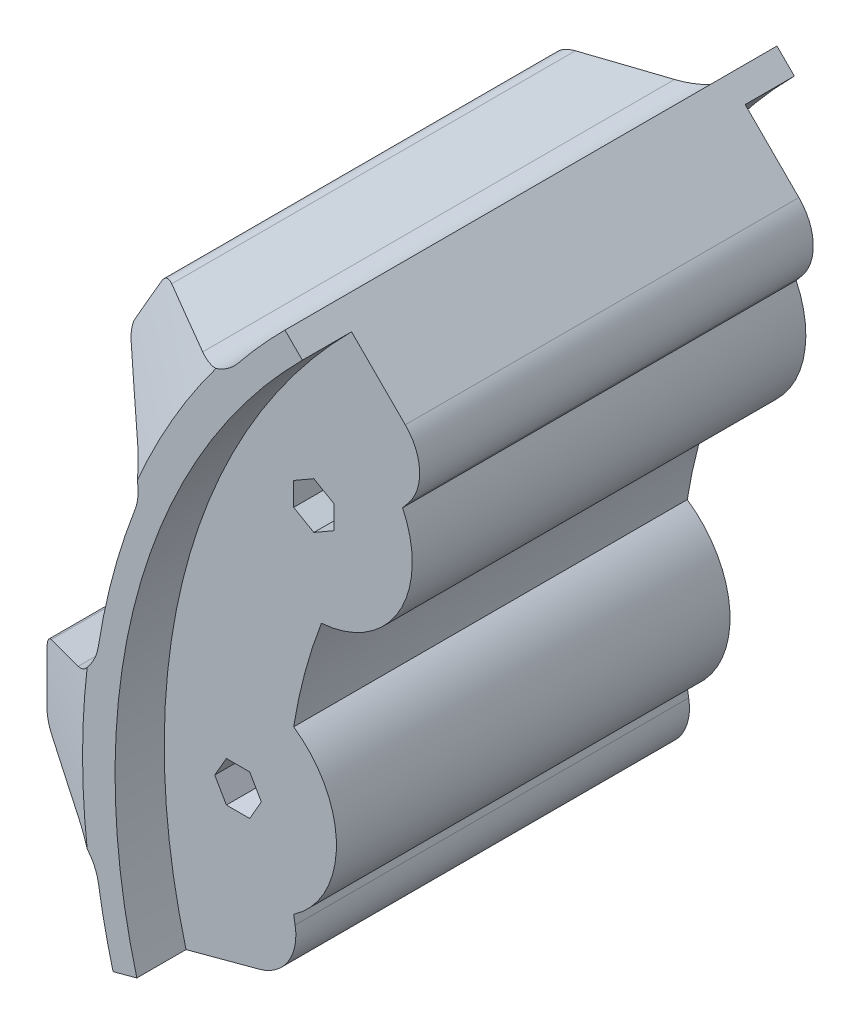
SolidWorks part; units mm, degrees
ref_plane "前视基准面" through (0, 0, 0) normal (0, 0, 1) x (1, 0, 0)
ref_plane "上视基准面" through (0, 0, 0) normal (0, 1, 0) x (1, 0, 0)
ref_plane "右视基准面" through (0, 0, 0) normal (1, 0, 0) x (0, 0, -1)
other "Configuration Table"
sketch "草图1" plane through (0, 0, 0) normal (0, 0, 1) x (1, 0, 0)
  circle A0 centre (0, 0) radius 115 construction
  circle A1 centre (0, 0) radius 105
  circle A2 centre (0, 0) radius 130
  dimension "D1" = 230
  dimension "D2" = 210
  dimension "D3" = 260
extrude "凸台-拉伸1" add sketch "草图1" along normal blind 80
sketch "草图2" plane through (0, 0, 80) normal (0, 0, 1) x (1, 0, 0)
  line L0 (62.2343, 99.5929) -> (59.8671, 103.6929)
  line L1 (4.1, 117.3671) -> (0, 119.7343)
  line L2 (0, 119.7343) -> (-4.1, 117.3671)
  line L3 (-4.1, 117.3671) -> (-4.1, 112.6329)
  line L4 (-4.1, 112.6329) -> (0, 110.2657)
  line L5 (0, 110.2657) -> (4.1, 112.6329)
  line L6 (4.1, 112.6329) -> (4.1, 117.3671)
  line L7 (59.8671, 95.4929) -> (62.2343, 99.5929)
  line L8 (55.1329, 95.4929) -> (59.8671, 95.4929)
  line L9 (52.7657, 99.5929) -> (55.1329, 95.4929)
  line L10 (55.1329, 103.6929) -> (52.7657, 99.5929)
  line L11 (59.8671, 103.6929) -> (55.1329, 103.6929)
  line L12 (103.6929, 55.1329) -> (103.6929, 59.8671)
  line L13 (99.5929, 52.7657) -> (103.6929, 55.1329)
  line L14 (95.4929, 55.1329) -> (99.5929, 52.7657)
  line L15 (95.4929, 59.8671) -> (95.4929, 55.1329)
  line L16 (99.5929, 62.2343) -> (95.4929, 59.8671)
  line L17 (103.6929, 59.8671) -> (99.5929, 62.2343)
  line L18 (117.3671, -4.1) -> (119.7343, 0)
  line L19 (112.6329, -4.1) -> (117.3671, -4.1)
  line L20 (110.2657, 0) -> (112.6329, -4.1)
  line L21 (112.6329, 4.1) -> (110.2657, 0)
  line L22 (117.3671, 4.1) -> (112.6329, 4.1)
  line L23 (119.7343, 0) -> (117.3671, 4.1)
  line L24 (99.5929, -62.2343) -> (103.6929, -59.8671)
  line L25 (95.4929, -59.8671) -> (99.5929, -62.2343)
  line L26 (95.4929, -55.1329) -> (95.4929, -59.8671)
  line L27 (99.5929, -52.7657) -> (95.4929, -55.1329)
  line L28 (103.6929, -55.1329) -> (99.5929, -52.7657)
  line L29 (103.6929, -59.8671) -> (103.6929, -55.1329)
  line L30 (55.1329, -103.6929) -> (59.8671, -103.6929)
  line L31 (52.7657, -99.5929) -> (55.1329, -103.6929)
  line L32 (55.1329, -95.4929) -> (52.7657, -99.5929)
  line L33 (59.8671, -95.4929) -> (55.1329, -95.4929)
  line L34 (62.2343, -99.5929) -> (59.8671, -95.4929)
  line L35 (59.8671, -103.6929) -> (62.2343, -99.5929)
  line L36 (-4.1, -117.3671) -> (0, -119.7343)
  line L37 (-4.1, -112.6329) -> (-4.1, -117.3671)
  line L38 (0, -110.2657) -> (-4.1, -112.6329)
  line L39 (4.1, -112.6329) -> (0, -110.2657)
  line L40 (4.1, -117.3671) -> (4.1, -112.6329)
  line L41 (0, -119.7343) -> (4.1, -117.3671)
  line L42 (-62.2343, -99.5929) -> (-59.8671, -103.6929)
  line L43 (-59.8671, -95.4929) -> (-62.2343, -99.5929)
  line L44 (-55.1329, -95.4929) -> (-59.8671, -95.4929)
  line L45 (-52.7657, -99.5929) -> (-55.1329, -95.4929)
  line L46 (-55.1329, -103.6929) -> (-52.7657, -99.5929)
  line L47 (-59.8671, -103.6929) -> (-55.1329, -103.6929)
  line L48 (-103.6929, -55.1329) -> (-103.6929, -59.8671)
  line L49 (-99.5929, -52.7657) -> (-103.6929, -55.1329)
  line L50 (-95.4929, -55.1329) -> (-99.5929, -52.7657)
  line L51 (-95.4929, -59.8671) -> (-95.4929, -55.1329)
  line L52 (-99.5929, -62.2343) -> (-95.4929, -59.8671)
  line L53 (-103.6929, -59.8671) -> (-99.5929, -62.2343)
  line L54 (-117.3671, 4.1) -> (-119.7343, 0)
  line L55 (-112.6329, 4.1) -> (-117.3671, 4.1)
  line L56 (-110.2657, 0) -> (-112.6329, 4.1)
  line L57 (-112.6329, -4.1) -> (-110.2657, 0)
  line L58 (-117.3671, -4.1) -> (-112.6329, -4.1)
  line L59 (-119.7343, 0) -> (-117.3671, -4.1)
  line L60 (-99.5929, 62.2343) -> (-103.6929, 59.8671)
  line L61 (-95.4929, 59.8671) -> (-99.5929, 62.2343)
  line L62 (-95.4929, 55.1329) -> (-95.4929, 59.8671)
  line L63 (-99.5929, 52.7657) -> (-95.4929, 55.1329)
  line L64 (-103.6929, 55.1329) -> (-99.5929, 52.7657)
  line L65 (-103.6929, 59.8671) -> (-103.6929, 55.1329)
  line L66 (-55.1329, 103.6929) -> (-59.8671, 103.6929)
  line L67 (-52.7657, 99.5929) -> (-55.1329, 103.6929)
  line L68 (-55.1329, 95.4929) -> (-52.7657, 99.5929)
  line L69 (-59.8671, 95.4929) -> (-55.1329, 95.4929)
  line L70 (-62.2343, 99.5929) -> (-59.8671, 95.4929)
  line L71 (-59.8671, 103.6929) -> (-62.2343, 99.5929)
  circle A0 centre (0, 0) radius 115 construction
  circle A1 centre (0, 115) radius 2.5 construction
  circle A2 centre (0, 115) radius 4.1 construction
  point P80 (0, 0)
  dimension "D1" = 230
  dimension "D2" = 5
  dimension "D3" = 4.7343
  dimension "D4" = 8.2
  dimension "D5" = 12
extrude "切除-拉伸1" cut sketch "草图2" against normal through all
sketch "草图5" plane through (0, 0, 80) normal (0, 0, 1) x (1, 0, 0)
  circle A0 centre (0, 0) radius 130
  circle A1 centre (0, 0) radius 150
  dimension "D1" = 260
  dimension "D2" = 300
extrude "凸台-拉伸2" add sketch "草图5" against normal blind 90 and the other way blind 10
sketch "草图7" plane through (0, 0, 80) normal (0, 0, 1) x (1, 0, 0)
  line L0 (0, 119.7343) -> (0, 110.2657) construction
  line L1 (0, 110.2657) -> (4.1, 112.6329) construction
  line L2 (-20, 115) -> (-7.5, 115)
  line L3 (7.5, 115) -> (20, 115)
  line L4 (40.1795, 109.5929) -> (51.0048, 103.3429)
  line L5 (63.9952, 95.8429) -> (74.8205, 89.5929)
  line L6 (89.5929, 74.8205) -> (95.8429, 63.9952)
  line L7 (103.3429, 51.0048) -> (109.5929, 40.1795)
  line L8 (115, 20) -> (115, 7.5)
  line L9 (115, -7.5) -> (115, -20)
  line L10 (109.5929, -40.1795) -> (103.3429, -51.0048)
  line L11 (95.8429, -63.9952) -> (89.5929, -74.8205)
  line L12 (74.8205, -89.5929) -> (63.9952, -95.8429)
  line L13 (51.0048, -103.3429) -> (40.1795, -109.5929)
  line L14 (20, -115) -> (7.5, -115)
  line L15 (-7.5, -115) -> (-20, -115)
  line L16 (-40.1795, -109.5929) -> (-51.0048, -103.3429)
  line L17 (-63.9952, -95.8429) -> (-74.8205, -89.5929)
  line L18 (-89.5929, -74.8205) -> (-95.8429, -63.9952)
  line L19 (-103.3429, -51.0048) -> (-109.5929, -40.1795)
  line L20 (-115, -20) -> (-115, -7.5)
  line L21 (-115, 7.5) -> (-115, 20)
  line L22 (-109.5929, 40.1795) -> (-103.3429, 51.0048)
  line L23 (-95.8429, 63.9952) -> (-89.5929, 74.8205)
  line L24 (-74.8205, 89.5929) -> (-63.9952, 95.8429)
  line L25 (-51.0048, 103.3429) -> (-40.1795, 109.5929)
  arc A0 (-7.5, 115) -> (7.5, 115) centre (0, 115) ccw
  arc A1 (-20, 115) -> (20, 115) centre (0, 115) ccw
  arc A2 (51.0048, 103.3429) -> (63.9952, 95.8429) centre (57.5, 99.5929) ccw
  arc A3 (40.1795, 109.5929) -> (74.8205, 89.5929) centre (57.5, 99.5929) ccw
  arc A4 (95.8429, 63.9952) -> (103.3429, 51.0048) centre (99.5929, 57.5) ccw
  arc A5 (89.5929, 74.8205) -> (109.5929, 40.1795) centre (99.5929, 57.5) ccw
  arc A6 (115, 7.5) -> (115, -7.5) centre (115, 0) ccw
  arc A7 (115, 20) -> (115, -20) centre (115, 0) ccw
  arc A8 (103.3429, -51.0048) -> (95.8429, -63.9952) centre (99.5929, -57.5) ccw
  arc A9 (109.5929, -40.1795) -> (89.5929, -74.8205) centre (99.5929, -57.5) ccw
  arc A10 (63.9952, -95.8429) -> (51.0048, -103.3429) centre (57.5, -99.5929) ccw
  arc A11 (74.8205, -89.5929) -> (40.1795, -109.5929) centre (57.5, -99.5929) ccw
  arc A12 (7.5, -115) -> (-7.5, -115) centre (0, -115) ccw
  arc A13 (20, -115) -> (-20, -115) centre (0, -115) ccw
  arc A14 (-51.0048, -103.3429) -> (-63.9952, -95.8429) centre (-57.5, -99.5929) ccw
  arc A15 (-40.1795, -109.5929) -> (-74.8205, -89.5929) centre (-57.5, -99.5929) ccw
  arc A16 (-95.8429, -63.9952) -> (-103.3429, -51.0048) centre (-99.5929, -57.5) ccw
  arc A17 (-89.5929, -74.8205) -> (-109.5929, -40.1795) centre (-99.5929, -57.5) ccw
  arc A18 (-115, -7.5) -> (-115, 7.5) centre (-115, 0) ccw
  arc A19 (-115, -20) -> (-115, 20) centre (-115, 0) ccw
  arc A20 (-103.3429, 51.0048) -> (-95.8429, 63.9952) centre (-99.5929, 57.5) ccw
  arc A21 (-109.5929, 40.1795) -> (-89.5929, 74.8205) centre (-99.5929, 57.5) ccw
  arc A22 (-63.9952, 95.8429) -> (-51.0048, 103.3429) centre (-57.5, 99.5929) ccw
  arc A23 (-74.8205, 89.5929) -> (-40.1795, 109.5929) centre (-57.5, 99.5929) ccw
  point P69 (0, 0)
  dimension "D1" = 15
  dimension "D2" = 40
  dimension "D3" = 12
extrude "凸台-拉伸3" add sketch "草图7" against normal blind 80
sketch "草图8" plane through (0, 0, 90) normal (0, 0, 1) x (1, 0, 0)
  line L0 (-7.5, 153.8167) -> (7.5, 153.8167)
  line L1 (7.5, 153.8167) -> (17.5, 128.8167)
  line L2 (-7.5, 153.8167) -> (-17.5, 128.8167)
  line L3 (-17.5, 128.8167) -> (17.5, 128.8167)
  line L4 (0, 153.8167) -> (0, 128.8167) construction
  line L5 (0, 128.8167) -> (0, 0)
  line L6 (70.4132, 136.9592) -> (83.4036, 129.4592)
  line L7 (70.4132, 136.9592) -> (49.2529, 120.3086)
  line L8 (83.4036, 129.4592) -> (79.5638, 102.8086)
  line L9 (49.2529, 120.3086) -> (79.5638, 102.8086)
  line L10 (129.4592, 83.4036) -> (136.9592, 70.4132)
  line L11 (129.4592, 83.4036) -> (102.8086, 79.5638)
  line L12 (136.9592, 70.4132) -> (120.3086, 49.2529)
  line L13 (102.8086, 79.5638) -> (120.3086, 49.2529)
  line L14 (153.8167, 7.5) -> (153.8167, -7.5)
  line L15 (153.8167, 7.5) -> (128.8167, 17.5)
  line L16 (153.8167, -7.5) -> (128.8167, -17.5)
  line L17 (128.8167, 17.5) -> (128.8167, -17.5)
  line L18 (136.9592, -70.4132) -> (129.4592, -83.4036)
  line L19 (136.9592, -70.4132) -> (120.3086, -49.2529)
  line L20 (129.4592, -83.4036) -> (102.8086, -79.5638)
  line L21 (120.3086, -49.2529) -> (102.8086, -79.5638)
  line L22 (83.4036, -129.4592) -> (70.4132, -136.9592)
  line L23 (83.4036, -129.4592) -> (79.5638, -102.8086)
  line L24 (70.4132, -136.9592) -> (49.2529, -120.3086)
  line L25 (79.5638, -102.8086) -> (49.2529, -120.3086)
  line L26 (7.5, -153.8167) -> (-7.5, -153.8167)
  line L27 (7.5, -153.8167) -> (17.5, -128.8167)
  line L28 (-7.5, -153.8167) -> (-17.5, -128.8167)
  line L29 (17.5, -128.8167) -> (-17.5, -128.8167)
  line L30 (-70.4132, -136.9592) -> (-83.4036, -129.4592)
  line L31 (-70.4132, -136.9592) -> (-49.2529, -120.3086)
  line L32 (-83.4036, -129.4592) -> (-79.5638, -102.8086)
  line L33 (-49.2529, -120.3086) -> (-79.5638, -102.8086)
  line L34 (-129.4592, -83.4036) -> (-136.9592, -70.4132)
  line L35 (-129.4592, -83.4036) -> (-102.8086, -79.5638)
  line L36 (-136.9592, -70.4132) -> (-120.3086, -49.2529)
  line L37 (-102.8086, -79.5638) -> (-120.3086, -49.2529)
  line L38 (-153.8167, -7.5) -> (-153.8167, 7.5)
  line L39 (-153.8167, -7.5) -> (-128.8167, -17.5)
  line L40 (-153.8167, 7.5) -> (-128.8167, 17.5)
  line L41 (-128.8167, -17.5) -> (-128.8167, 17.5)
  line L42 (-136.9592, 70.4132) -> (-129.4592, 83.4036)
  line L43 (-136.9592, 70.4132) -> (-120.3086, 49.2529)
  line L44 (-129.4592, 83.4036) -> (-102.8086, 79.5638)
  line L45 (-120.3086, 49.2529) -> (-102.8086, 79.5638)
  line L46 (-83.4036, 129.4592) -> (-70.4132, 136.9592)
  line L47 (-83.4036, 129.4592) -> (-79.5638, 102.8086)
  line L48 (-70.4132, 136.9592) -> (-49.2529, 120.3086)
  line L49 (-79.5638, 102.8086) -> (-49.2529, 120.3086)
  circle A1 centre (0, 0) radius 130 construction
  circle A2 centre (0, 0) radius 130 construction
  point P59 (0, 0)
  point P91 (0, 0)
  dimension "D1" = 15
  dimension "D2" = 35
  dimension "D3" = 128.8167
  dimension "D4" = 25
  dimension "D5" = 12
extrude "凸台-拉伸4" add sketch "草图8" against normal through all
sketch "草图10" plane through (0, 0, 90) normal (0, 0, 1) x (1, 0, 0)
  line L0 (-9.1381, 149.7214) -> (-15.3782, 134.1213)
  line L1 (9.1381, 149.7214) -> (15.3782, 134.1213)
  line L2 (-7.5, 153.8167) -> (-9.1381, 149.7214) construction
  line L3 (7.5, 153.8167) -> (9.1381, 149.7214) construction
  line L4 (66.9468, 134.2316) -> (53.7427, 123.8415)
  line L5 (82.7746, 125.0935) -> (80.3785, 108.4633)
  line L6 (125.0935, 82.7746) -> (108.4633, 80.3785)
  line L7 (134.2316, 66.9468) -> (123.8415, 53.7427)
  line L8 (149.7214, 9.1381) -> (134.1213, 15.3782)
  line L9 (149.7214, -9.1381) -> (134.1213, -15.3782)
  line L10 (134.2316, -66.9468) -> (123.8415, -53.7427)
  line L11 (125.0935, -82.7746) -> (108.4633, -80.3785)
  line L12 (82.7746, -125.0935) -> (80.3785, -108.4633)
  line L13 (66.9468, -134.2316) -> (53.7427, -123.8415)
  line L14 (9.1381, -149.7214) -> (15.3782, -134.1213)
  line L15 (-9.1381, -149.7214) -> (-15.3782, -134.1213)
  line L16 (-66.9468, -134.2316) -> (-53.7427, -123.8415)
  line L17 (-82.7746, -125.0935) -> (-80.3785, -108.4633)
  line L18 (-125.0935, -82.7746) -> (-108.4633, -80.3785)
  line L19 (-134.2316, -66.9468) -> (-123.8415, -53.7427)
  line L20 (-149.7214, -9.1381) -> (-134.1213, -15.3782)
  line L21 (-149.7214, 9.1381) -> (-134.1213, 15.3782)
  line L22 (-134.2316, 66.9468) -> (-123.8415, 53.7427)
  line L23 (-125.0935, 82.7746) -> (-108.4633, 80.3785)
  line L24 (-82.7746, 125.0935) -> (-80.3785, 108.4633)
  line L25 (-66.9468, 134.2316) -> (-53.7427, 123.8415)
  arc A0 (-123.8415, 53.7427) -> (-134.1213, 15.3782) centre (0, 0) ccw
  arc A1 (-134.1213, -15.3782) -> (-123.8415, -53.7427) centre (0, 0) ccw
  arc A14 (-82.7746, 125.0935) -> (-125.0935, 82.7746) centre (0, 0) ccw
  arc A15 (-134.2316, 66.9468) -> (-149.7214, 9.1381) centre (0, 0) ccw
  arc A16 (-149.7214, -9.1381) -> (-134.2316, -66.9468) centre (0, 0) ccw
  arc A17 (-125.0935, -82.7746) -> (-82.7746, -125.0935) centre (0, 0) ccw
  arc A18 (-66.9468, -134.2316) -> (-9.1381, -149.7214) centre (0, 0) ccw
  arc A19 (9.1381, -149.7214) -> (66.9468, -134.2316) centre (0, 0) ccw
  arc A20 (82.7746, -125.0935) -> (125.0935, -82.7746) centre (0, 0) ccw
  arc A21 (134.2316, -66.9468) -> (149.7214, -9.1381) centre (0, 0) ccw
  arc A22 (149.7214, 9.1381) -> (134.2316, 66.9468) centre (0, 0) ccw
  arc A23 (125.0935, 82.7746) -> (82.7746, 125.0935) centre (0, 0) ccw
  arc A24 (66.9468, 134.2316) -> (9.1381, 149.7214) centre (0, 0) ccw
  arc A25 (-9.1381, 149.7214) -> (-66.9468, 134.2316) centre (0, 0) ccw
  arc A26 (53.7427, 123.8415) -> (15.3782, 134.1213) centre (0, 0) ccw
  arc A27 (-15.3782, 134.1213) -> (-53.7427, 123.8415) centre (0, 0) ccw
  arc A28 (-80.3785, 108.4633) -> (-108.4633, 80.3785) centre (0, 0) ccw
  arc A29 (-108.4633, -80.3785) -> (-80.3785, -108.4633) centre (0, 0) ccw
  arc A30 (-53.7427, -123.8415) -> (-15.3782, -134.1213) centre (0, 0) ccw
  arc A31 (15.3782, -134.1213) -> (53.7427, -123.8415) centre (0, 0) ccw
  arc A32 (80.3785, -108.4633) -> (108.4633, -80.3785) centre (0, 0) ccw
  arc A33 (123.8415, -53.7427) -> (134.1213, -15.3782) centre (0, 0) ccw
  arc A34 (134.1213, 15.3782) -> (123.8415, 53.7427) centre (0, 0) ccw
  arc A35 (108.4633, 80.3785) -> (80.3785, 108.4633) centre (0, 0) ccw
  point P61 (0, 0)
  dimension "D2" = 270
  dimension "D1" = 12
extrude "切除-拉伸4" cut sketch "草图10" against normal through all
fillet "圆角2" radius 10 24 edges at (-134.1213, -15.3782, 40) (-123.8415, -53.7427, 40) (-108.4633, -80.3785, 40) (-80.3785, -108.4633, 40) (-53.7427, -123.8415, 40) (-15.3782, -134.1213, 40) (15.3782, -134.1213, 40) (53.7427, -123.8415, 40) (80.3785, -108.4633, 40) (108.4633, -80.3785, 40) (123.8415, -53.7427, 40) (134.1213, -15.3782, 40) (134.1213, 15.3782, 40) (123.8415, 53.7427, 40) (80.3785, 108.4633, 40) (108.4633, 80.3785, 40) (-134.1213, 15.3782, 40) (-123.8415, 53.7427, 40) (53.7427, 123.8415, 40) (15.3782, 134.1213, 40) (-108.4633, 80.3785, 40) (-80.3785, 108.4633, 40) (-15.3782, 134.1213, 40) (-53.7427, 123.8415, 40)
fillet "圆角3" radius 3 24 edges at (70.4132, -136.9592, 40) (83.4036, -129.4592, 40) (129.4592, -83.4036, 40) (136.9592, -70.4132, 40) (153.8167, -7.5, 40) (153.8167, 7.5, 40) (136.9592, 70.4132, 40) (129.4592, 83.4036, 40) (83.4036, 129.4592, 40) (70.4132, 136.9592, 40) (7.5, 153.8167, 40) (-70.4132, 136.9592, 40) (-83.4036, 129.4592, 40) (-129.4592, 83.4036, 40) (-136.9592, 70.4132, 40) (-153.8167, 7.5, 40) (-153.8167, -7.5, 40) (-136.9592, -70.4132, 40) (-129.4592, -83.4036, 40) (-83.4036, -129.4592, 40) (-70.4132, -136.9592, 40) (-7.5, -153.8167, 40) (7.5, -153.8167, 40) (-7.5, 153.8167, 40)
sketch "草图11" plane through (0, 0, 0) normal (0, 1, 0) x (1, 0, 0)
  line L0 (0, 0) -> (0, 60) construction
  line L1 (-153.8167, -40) -> (153.8167, -40) construction
  line L3 (-50, 60) -> (-160, -3.5085)
  line L4 (-153.8167, -90) -> (-153.8167, 10) construction
  line L5 (153.8167, 10) -> (153.8167, -90) construction
  line L7 (-160, -140) -> (-160, -76.4915)
  line L8 (-50, 60) -> (-160, 60)
  line L9 (-160, 60) -> (-160, -3.5085)
  line L10 (-50, -140) -> (-160, -140)
  line L11 (-50, -140) -> (-160, -76.4915)
  dimension "D1" = 60
  dimension "D2" = 30
  dimension "D3" = 100
  dimension "D4" = 320
revolve "切除-旋转4" cut sketch "草图11" angle 360 about L0
sketch "草图12" plane through (0, 0, 80) normal (0, 0, 1) x (1, 0, 0)
  line L0 (0, 0) -> (-95.4594, 95.4594) construction
  line L1 (0, 0) -> (-130.4, -34.9406) construction
  line L2 (0, 0) -> (-141.4214, 141.4214)
  line L3 (0, 0) -> (-193.1852, -51.7638)
  arc A0 (-84.8238, 105.0234) -> (-105.0234, 84.8238) centre (0, 0) ccw construction
  arc A1 (-133.3649, -20.9478) -> (-125.9713, -48.5411) centre (0, 0) ccw construction
  arc A2 (-193.1852, -51.7638) -> (-141.4214, 141.4214) centre (0, 0) ccw
  dimension "D1" = 200
  dimension "D2" = 60
extrude "切除-拉伸5" cut sketch "草图12" against normal through all and the other way through all
fillet "圆角4" radius 10 2 edges at (-74.2462, 74.2462, 40) (-101.4222, -27.176, 40)
